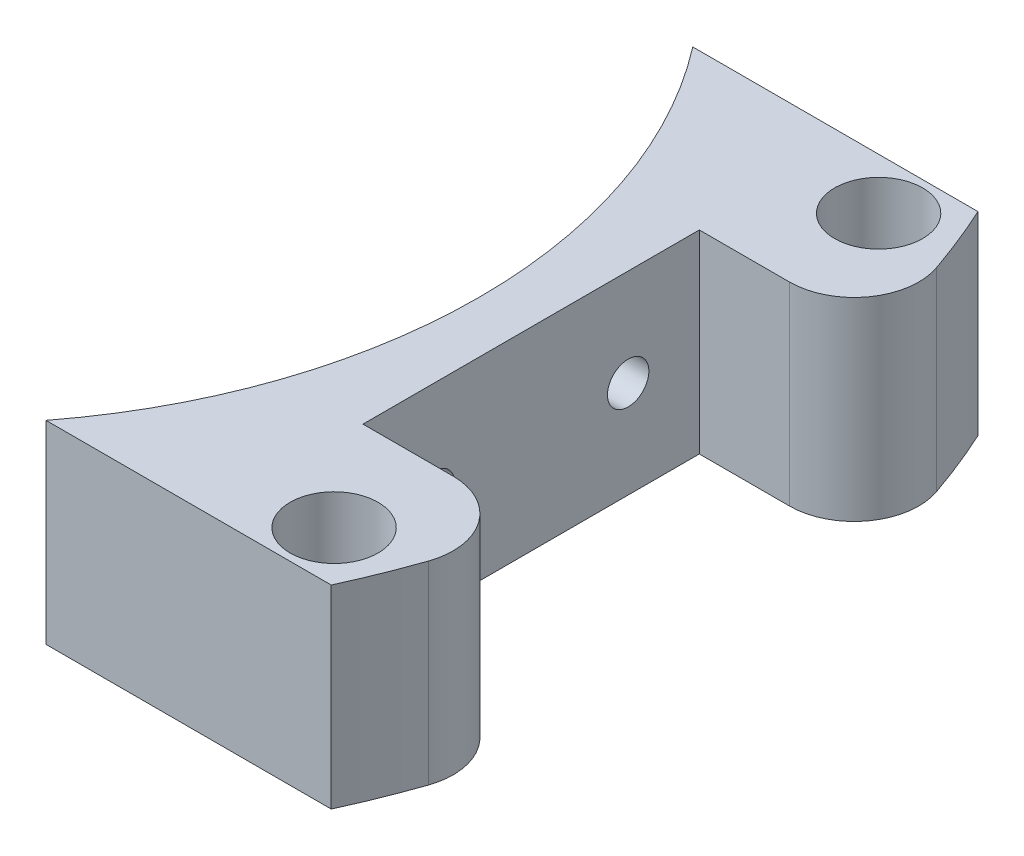
SolidWorks part; units mm, degrees
ref_plane "前视基准面" through (0, 0, 0) normal (0, 0, 1) x (1, 0, 0)
ref_plane "上视基准面" through (0, 0, 0) normal (0, 1, 0) x (1, 0, 0)
ref_plane "右视基准面" through (0, 0, 0) normal (1, 0, 0) x (0, 0, -1)
other "Configuration Table"
sketch "草图1" plane through (0, 0, 0) normal (0, 1, 0) x (1, 0, 0)
  line L3 (98.223, -107.4405) -> (93.8568, -95.4444)
  line L4 (-40.4497, 75.7097) -> (22.0464, 75.7097)
  line L5 (-7.9536, 50.7097) -> (22.0464, 50.7097)
  line L6 (-7.9536, 50.7097) -> (-7.9536, 100.7097)
  line L7 (-7.9536, 100.7097) -> (22.0464, 100.7097)
  line L8 (22.0464, 50.7097) -> (22.0464, 100.7097)
  circle A3 centre (-40.4497, 75.7097) radius 30
  circle A13 centre (10.3636, 96.7573) radius 3.4
  circle A14 centre (10.3636, 54.6621) radius 3.4
  circle A15 centre (-40.4497, 75.7097) radius 41
  circle A16 centre (-40.4497, 75.7097) radius 60
  dimension "D1" = 60
  dimension "D2" = 6.8
  dimension "D8" = 82
  dimension "D11" = 120
  dimension "D3" = 10.3636
  dimension "D4" = 40.4497
  dimension "D5" = 54.6621
  dimension "D6" = 75.7097
  dimension "D7" = 96.7573
  dimension "D9" = 50
  dimension "D10" = 30
extrude "凸台-拉伸2" add sketch "草图1" along normal blind 15 contours A15 L5 L8 L4 A14 | A15 L4 L8 L7 A13
sketch "草图2" plane through (0, 15, 0) normal (0, 1, 0) x (1, 0, 0)
  line L0 (-40.4497, 75.7097) -> (19.5503, 75.7097)
  line L1 (24.5503, 88.7097) -> (4.5503, 88.7097)
  line L2 (24.5503, 88.7097) -> (24.5503, 62.7097)
  line L3 (24.5503, 62.7097) -> (4.5503, 62.7097)
  line L4 (4.5503, 88.7097) -> (4.5503, 62.7097)
  line L6 (-7.9536, 50.7097) -> (14.0938, 50.7097)
  line L7 (14.0938, 100.7097) -> (-7.9536, 100.7097)
  line L8 (-7.9536, 50.7097) -> (14.0938, 50.7097)
  line L9 (14.0938, 100.7097) -> (-7.9536, 100.7097)
  arc A3 (14.0938, 50.7097) -> (14.0938, 100.7097) centre (-40.4497, 75.7097) ccw
  arc A4 (-7.9536, 50.7097) -> (-7.9536, 100.7097) centre (-40.4497, 75.7097) ccw
  arc A5 (14.0938, 50.7097) -> (14.0938, 100.7097) centre (-40.4497, 75.7097) ccw
  arc A6 (-7.9536, 50.7097) -> (-7.9536, 100.7097) centre (-40.4497, 75.7097) ccw
  arc M12 (14.0938, 50.7097) -> (14.0938, 100.7097) centre (-40.4497, 75.7097) ccw
  dimension "D1" = 0
  dimension "D2" = 45
  dimension "D3" = 13
  dimension "D4" = 13
  dimension "D5" = 20
extrude "切除-拉伸1" cut sketch "草图2" against normal through all contours L1 L4 L0 M12 | L0 L4 L3 M12
sketch "草图4" plane through (4.5503, 0, 0) normal (1, 0, 0) x (0, 0, -1)
  line L0 (62.7097, 7.5) -> (88.7097, 7.5)
  line L1 (62.7097, 0) -> (62.7097, 15) construction
  line L2 (88.7097, 0) -> (88.7097, 15) construction
  line L3 (75.7097, 15) -> (75.7097, 0)
  line L4 (88.7097, 15) -> (62.7097, 15) construction
  line L5 (88.7097, 0) -> (62.7097, 0) construction
  circle A0 centre (68.2097, 7.5) radius 1.6
  circle A1 centre (83.2097, 7.5) radius 1.6
  dimension "D1" = 7.5
  dimension "D2" = 7.5
  dimension "D3" = 3.2
  dimension "D4" = 3.2
extrude "切除-拉伸2" cut sketch "草图4" against normal through all contours L0 A1 | L0 A1 | L0 A0 | L0 A0
ref_plane "基准面1" through (-7.9536, 0, 0) normal (-1, 0, 0) x (0, 0, 1)
sketch "草图6" plane through (-7.9536, 0, 0) normal (-1, 0, 0) x (0, 0, 1)
  circle A0 centre (-83.2097, 7.5) radius 1.6 construction
  circle A1 centre (-83.2097, 7.5) radius 1.6
  circle A2 centre (-68.2097, 7.5) radius 1.6 construction
  circle A3 centre (-68.2097, 7.5) radius 1.6
  circle A4 centre (-83.2097, 7.5) radius 3.5
  circle A5 centre (-68.2097, 7.5) radius 3.5
  dimension "D1" = 7
  dimension "D2" = 7
extrude "切除-拉伸3" cut sketch "草图6" against normal blind 10
fillet "圆角1" radius 5 2 edges at (18.125, 7.5, -88.7097) (18.125, 7.5, -62.7097)
